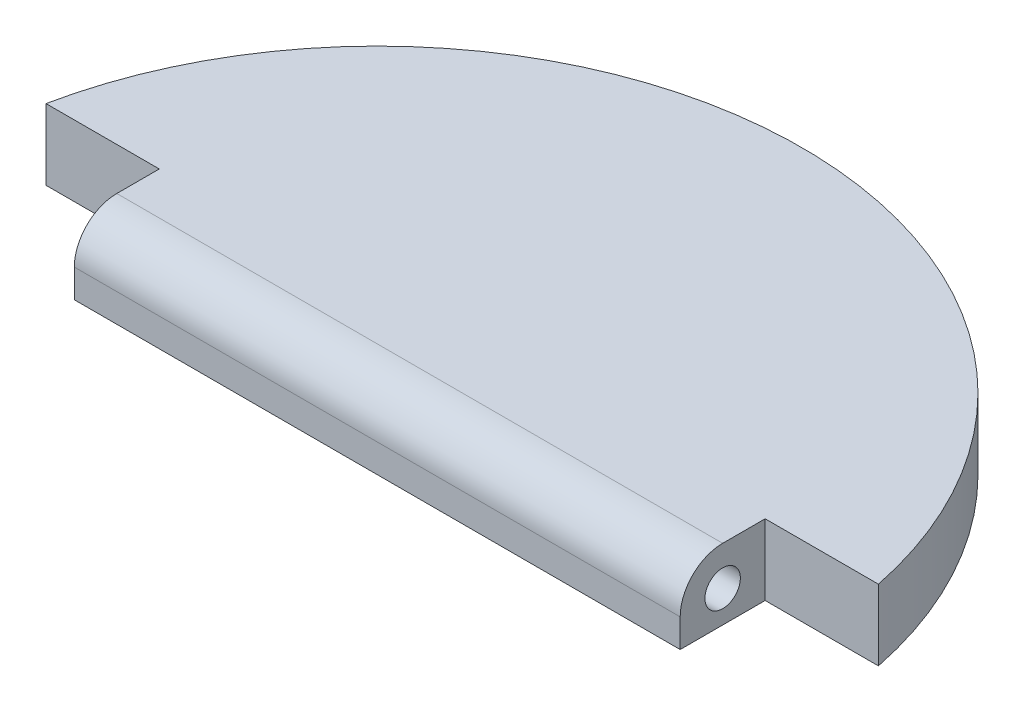
SolidWorks part; units mm, degrees
ref_plane "Front Plane" through (0, 0, 0) normal (0, 0, 1) x (1, 0, 0)
ref_plane "Top Plane" through (0, 0, 0) normal (0, 1, 0) x (1, 0, 0)
ref_plane "Right Plane" through (0, 0, 0) normal (1, 0, 0) x (0, 0, -1)
sketch "Sketch1" plane through (0, 0, 0) normal (0, 1, 0) x (1, 0, 0)
  line L0 (-30, 0) -> (30, 0)
  arc A0 (30, 0) -> (-30, 0) centre (0, 0) ccw
  dimension "D1" = 60
extrude "Boss-Extrude1" add sketch "Sketch1" along normal blind 5
sketch "Sketch5" plane through (0, 5, 0) normal (0, 1, 0) x (1, 0, 0)
  line L0 (-21.3939, 0) -> (-21.3939, 6)
  line L1 (-30, 0) -> (30, 0) construction
  line L2 (-21.3939, 6) -> (-29.3939, 6)
  line L3 (-30, 0) -> (-21.3939, 0)
  line L4 (0, -2.75) -> (0, 2.75) construction
  line L5 (21.3939, 6) -> (29.3939, 6)
  line L6 (21.3939, 0) -> (21.3939, 6)
  line L7 (30, 0) -> (21.3939, 0)
  arc A0 (30, 0) -> (-30, 0) centre (0, 0) ccw construction
  arc A1 (-29.3939, 6) -> (-30, 0) centre (0, 0) ccw
  arc A2 (29.3939, 6) -> (30, 0) centre (0, 0) cw
  dimension "D1" = 8
  dimension "D2" = 6
extrude "Cut-Extrude1" cut sketch "Sketch5" against normal blind 10
fillet "Fillet2" radius 3 1 edges at (0, 5, 0)
sketch "Sketch6" plane through (21.3939, 0, 0) normal (1, 0, 0) x (0, 0, -1)
  line L0 (6, 0) -> (0, 0) construction
  line L1 (0, 0) -> (0, 2) construction
  circle A0 centre (3, 2.25) radius 1.25
  dimension "D1" = 2.5
  dimension "D2" = 2.25
  dimension "D3" = 3
extrude "Cut-Extrude2" cut sketch "Sketch6" against normal blind 3
sketch "Sketch7" plane through (-21.3939, 0, 0) normal (-1, 0, 0) x (0, 0, 1)
  line L0 (0, 0) -> (0, 2) construction
  line L1 (0, 0) -> (-6, 0) construction
  circle A0 centre (-3, 2.25) radius 1.25
  dimension "D1" = 2.5
  dimension "D2" = 3
  dimension "D3" = 2.25
extrude "Cut-Extrude3" cut sketch "Sketch7" against normal blind 3
